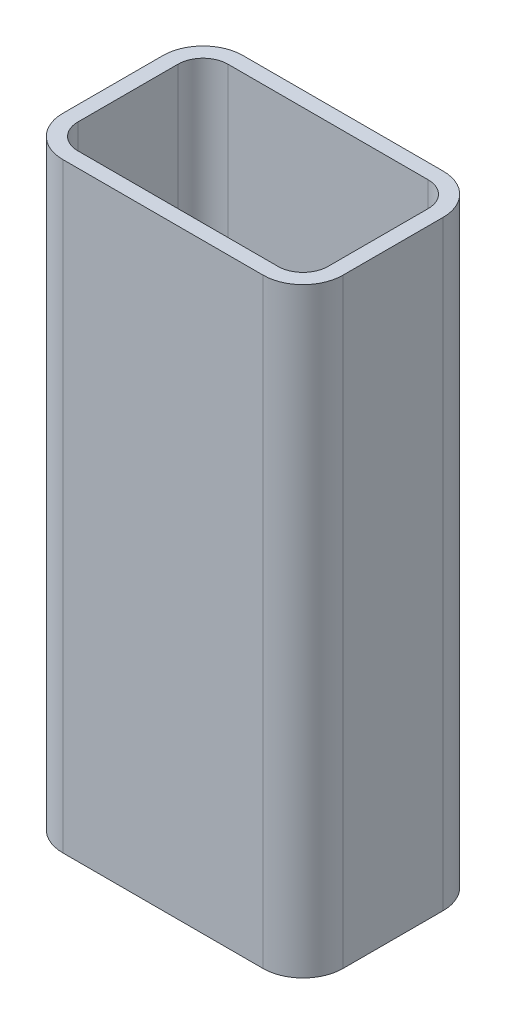
SolidWorks part; units mm, degrees
ref_plane "Front Plane" through (0, 0, 0) normal (0, 0, 1) x (1, 0, 0)
ref_plane "Top Plane" through (0, 0, 0) normal (0, 1, 0) x (1, 0, 0)
ref_plane "Right Plane" through (0, 0, 0) normal (1, 0, 0) x (0, 0, -1)
sketch "Sketch1" plane through (0, 0, 0) normal (0, 1, 0) x (1, 0, 0)
  line L1 (-20, -15) -> (20, -15)
  line L2 (-25, -10) -> (-25, 10)
  line L3 (-20, 15) -> (20, 15)
  line L4 (25, -10) -> (25, 10)
  line L5 (-25, -15) -> (25, 15) construction
  line L6 (-25, 15) -> (25, -15) construction
  arc A0 (-25, 10) -> (-20, 15) centre (-20, 10) cw
  arc A1 (-20, -15) -> (-25, -10) centre (-20, -10) cw
  arc A2 (20, -15) -> (25, -10) centre (20, -10) ccw
  arc A3 (20, 15) -> (25, 10) centre (20, 10) cw
  point P0 (0, 0)
  dimension "D3" = 5
  dimension "shortendrectangle" = 30
  dimension "longendrectangle" = 50
extrude "Extrude-Thin1" add sketch "Sketch1" along normal mid plane 120 thin
sketch "Sketch2" plane through (0, 0, -18) normal (0, 0, -1) x (-1, 0, 0)
  line L0 (0, 43.2855) -> (0, -46.4479) construction
  line L1 (18.7768, 0) -> (-16.2074, 0) construction
  line L7 (6, 45) -> (6, -45)
  line L10 (-6, 45) -> (-6, -45)
  arc A0 (-6, 45) -> (6, 45) centre (0, 45) cw
  arc A1 (-6, -45) -> (6, -45) centre (0, -45) ccw
  point P7 (-6, 0)
  point P10 (6, 0)
  dimension "D1" = 90
  dimension "D2" = 90
  dimension "D3" = 0
  dimension "D4" = 0
  dimension "D5" = 12
  dimension "D6" = 6
extrude "Cut-Extrude1" [suppressed] cut sketch "Sketch2" against normal through all
